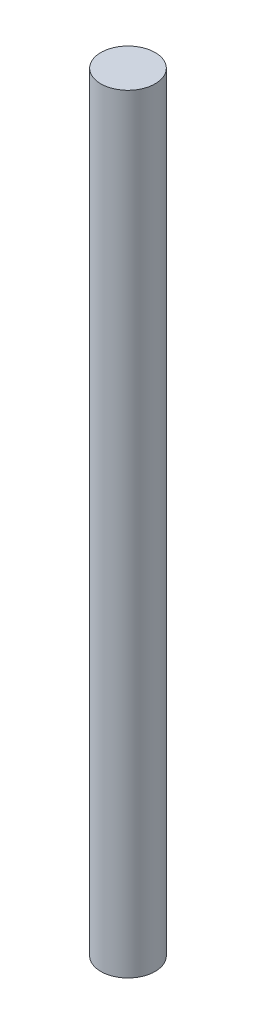
SolidWorks part; units mm, degrees
material "NON SPECIFIE"
ref_plane "Plan de face" through (0, 0, 0) normal (0, 0, 1) x (1, 0, 0)
ref_plane "Plan de dessus" through (0, 0, 0) normal (0, 1, 0) x (1, 0, 0)
ref_plane "Plan de droite" through (0, 0, 0) normal (1, 0, 0) x (0, 0, -1)
sketch "Sketch1" plane through (0, 0, 0) normal (0, 1, 0) x (1, 0, 0)
  circle A0 centre (0, 0) radius 6
  dimension "D1" = 12
extrude "Boss-Extrude1" add sketch "Sketch1" along normal blind 170
